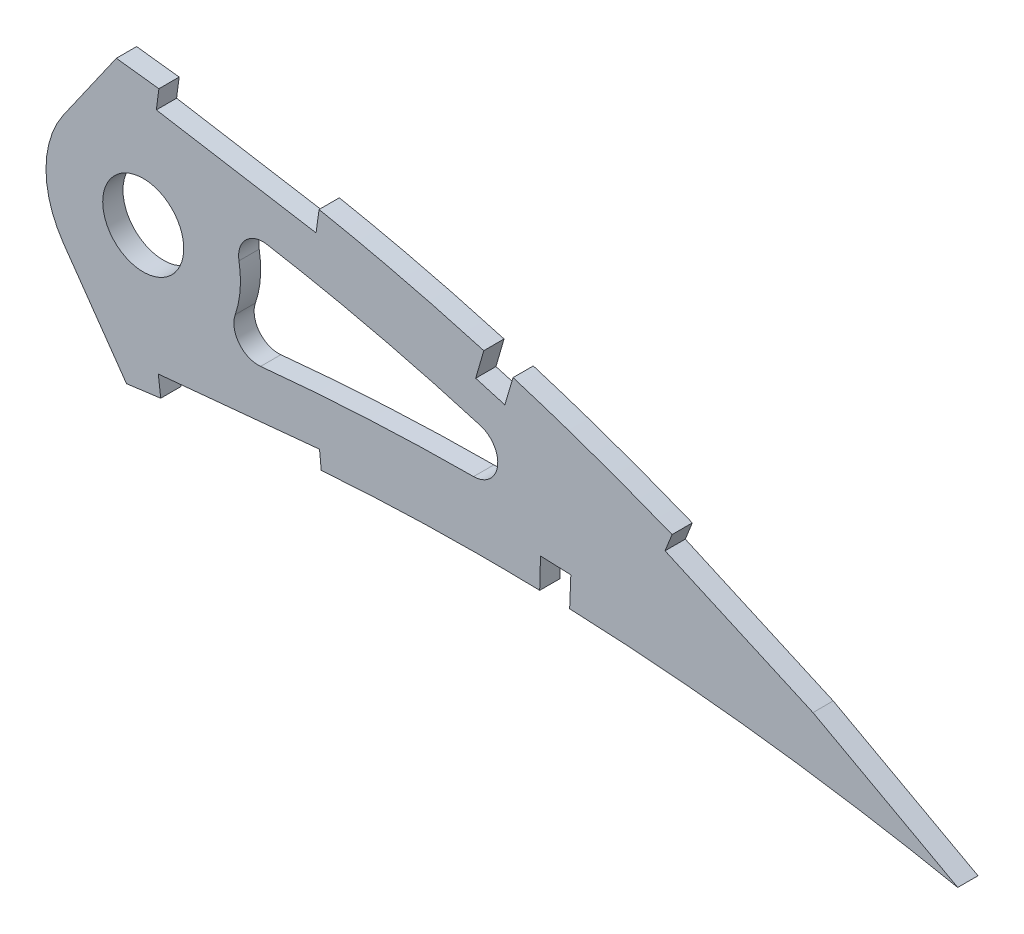
SolidWorks part; units mm, degrees
ref_plane "Front Plane" through (0, 0, 0) normal (0, 0, 1) x (1, 0, 0)
ref_plane "Top Plane" through (0, 0, 0) normal (0, 1, 0) x (1, 0, 0)
ref_plane "Right Plane" through (0, 0, 0) normal (1, 0, 0) x (0, 0, -1)
curve "Curve1"
  spline degree 3 poles (418.0125, 0.6517, 0) (417.9804, 0.6715, 0) (417.8525, 0.7505, 0) (417.5642, 0.9274, 0) (417.084, 1.2219, 0) (416.4119, 1.6322, 0) (415.5483, 2.157, 0) (414.4927, 2.7927, 0) (413.2459, 3.5372, 0) (411.8081, 4.387, 0) (410.1795, 5.3382, 0) (408.3608, 6.3869, 0) (406.352, 7.527, 0) (404.1539, 8.7541, 0) (401.7673, 10.0622, 0) (399.1927, 11.4455, 0) (396.4309, 12.8968, 0) (393.4831, 14.4101, 0) (390.3497, 15.9768, 0) (387.0323, 17.5905, 0) (383.532, 19.2431, 0) (379.8498, 20.9259, 0) (375.9881, 22.6319, 0) (371.9478, 24.3506, 0) (367.7312, 26.0745, 0) (363.3401, 27.7938, 0) (358.7771, 29.5006, 0) (354.0441, 31.184, 0) (349.1444, 32.8365, 0) (344.0806, 34.4474, 0) (338.8562, 36.008, 0) (333.4742, 37.5082, 0) (327.9392, 38.9402, 0) (322.2547, 40.2936, 0) (316.4254, 41.5594, 0) (310.456, 42.7299, 0) (304.3515, 43.7936, 0) (298.1289, 44.7494, 0) (291.8882, 45.5445, 0) (285.6603, 46.3243, 0) (279.4418, 47.0569, 0) (273.1472, 47.7584, 0) (266.7827, 48.425, 0) (260.3545, 49.0544, 0) (253.8692, 49.6441, 0) (247.3335, 50.1923, 0) (240.7538, 50.6959, 0) (234.1369, 51.1541, 0) (227.4895, 51.5628, 0) (220.8185, 51.9218, 0) (214.1308, 52.2286, 0) (207.4334, 52.481, 0) (200.7332, 52.6776, 0) (194.0374, 52.8164, 0) (187.3531, 52.8966, 0) (180.6873, 52.916, 0) (174.0473, 52.8742, 0) (167.44, 52.7698, 0) (160.8726, 52.6014, 0) (154.3521, 52.3686, 0) (147.8856, 52.0716, 0) (141.4801, 51.7078, 0) (135.1426, 51.2797, 0) (128.8802, 50.7853, 0) (122.6997, 50.2246, 0) (116.6076, 49.5999, 0) (110.6107, 48.9095, 0) (104.7154, 48.1553, 0) (98.9282, 47.3389, 0) (93.2555, 46.4598, 0) (87.7035, 45.5205, 0) (82.2781, 44.522, 0) (76.9851, 43.4673, 0) (71.8302, 42.3565, 0) (66.8189, 41.1931, 0) (61.9564, 39.979, 0) (57.2479, 38.7165, 0) (52.6982, 37.4086, 0) (48.3119, 36.0583, 0) (44.0941, 34.667, 0) (40.048, 33.2401, 0) (36.1786, 31.7785, 0) (32.4888, 30.2868, 0) (28.983, 28.767, 0) (25.6637, 27.2237, 0) (22.5348, 25.6586, 0) (19.5984, 24.0762, 0) (16.8576, 22.4789, 0) (14.3149, 20.8697, 0) (11.9714, 19.2526, 0) (9.8303, 17.6287, 0) (7.8925, 16.002, 0) (6.159, 14.375, 0) (4.6325, 12.7489, 0) (3.3127, 11.1265, 0) (2.2016, 9.5091, 0) (1.2991, 7.8983, 0) (0.6075, 6.2951, 0) (0.126, 4.7006, 0) (-0.1376, 3.117, 0) (-0.2032, 1.5431, 0) (-0.0676, 0.5136, 0) (0, 0, 0) knots 0 0 0 0 0.000254 0.001015 0.002283 0.004057 0.006331 0.009105 0.012374 0.016134 0.02038 0.025106 0.030306 0.035972 0.0421 0.048678 0.055702 0.06316 0.071046 0.07935 0.088063 0.097176 0.106678 0.116562 0.126814 0.137428 0.148394 0.1597 0.171338 0.183298 0.19557 0.208144 0.221012 0.234162 0.247587 0.261277 0.275223 0.289414 0.303771 0.317689 0.331784 0.34604 0.360444 0.374983 0.38964 0.404403 0.419257 0.434187 0.449177 0.464215 0.479284 0.49437 0.509458 0.524532 0.539579 0.554583 0.56953 0.584403 0.599191 0.613877 0.628447 0.642889 0.657186 0.671326 0.685294 0.699078 0.712665 0.726043 0.739198 0.752118 0.764792 0.777208 0.789356 0.801224 0.812804 0.824083 0.835055 0.84571 0.856038 0.866034 0.875689 0.884998 0.893953 0.902553 0.910789 0.918661 0.926166 0.933303 0.940071 0.946475 0.952518 0.958205 0.963547 0.968557 0.97325 0.977651 0.981787 0.985694 0.989415 0.993001 0.996508 1 1 1 1
curve "Curve2"
  spline degree 3 poles (0, 0, 0) (0.1073, -0.5067, 0) (0.3225, -1.5225, 0) (0.9071, -2.9849, 0) (1.6803, -4.3906, 0) (2.6581, -5.736, 0) (3.8343, -7.0207, 0) (5.206, -8.246, 0) (6.772, -9.4112, 0) (8.5303, -10.5159, 0) (10.4783, -11.5612, 0) (12.6138, -12.5465, 0) (14.9348, -13.4715, 0) (17.4389, -14.3348, 0) (20.1229, -15.1379, 0) (22.9843, -15.8787, 0) (26.0199, -16.5584, 0) (29.2267, -17.1751, 0) (32.6013, -17.7296, 0) (36.1401, -18.2214, 0) (39.8395, -18.651, 0) (43.6959, -19.0173, 0) (47.7054, -19.3212, 0) (51.8641, -19.5629, 0) (56.168, -19.7432, 0) (60.6128, -19.8613, 0) (65.1943, -19.9191, 0) (69.9083, -19.9175, 0) (74.7502, -19.8561, 0) (79.7159, -19.7382, 0) (84.8006, -19.5631, 0) (89.9997, -19.3329, 0) (95.3085, -19.05, 0) (100.7222, -18.7153, 0) (106.2362, -18.3302, 0) (111.8455, -17.8979, 0) (117.5452, -17.4195, 0) (123.3302, -16.8976, 0) (129.1955, -16.3351, 0) (135.1358, -15.7335, 0) (141.1461, -15.0958, 0) (147.221, -14.4241, 0) (153.3552, -13.7218, 0) (159.5432, -12.9903, 0) (165.7798, -12.2338, 0) (172.059, -11.4536, 0) (178.3757, -10.6529, 0) (184.7241, -9.8353, 0) (191.0984, -9.0009, 0) (197.493, -8.1554, 0) (203.902, -7.2983, 0) (210.3197, -6.4339, 0) (216.7401, -5.5649, 0) (223.157, -4.6917, 0) (229.5648, -3.8177, 0) (235.9575, -2.9455, 0) (242.3289, -2.075, 0) (248.6732, -1.2107, 0) (254.984, -0.3523, 0) (261.2554, 0.4983, 0) (267.4816, 1.3385, 0) (273.6565, 2.1675, 0) (279.7739, 2.9846, 0) (285.8276, 3.7901, 0) (291.7208, 4.5595, 0) (297.4382, 5.334, 0) (302.999, 5.9689, 0) (308.4906, 6.5107, 0) (313.9186, 6.955, 0) (319.2766, 7.3081, 0) (324.5584, 7.5724, 0) (329.7577, 7.7517, 0) (334.868, 7.8514, 0) (339.8828, 7.8739, 0) (344.7953, 7.8264, 0) (349.5992, 7.7127, 0) (354.2877, 7.538, 0) (358.8543, 7.3082, 0) (363.2925, 7.0294, 0) (367.5956, 6.7058, 0) (371.7576, 6.345, 0) (375.7722, 5.9523, 0) (379.6331, 5.5321, 0) (383.3347, 5.0933, 0) (386.8711, 4.6386, 0) (390.237, 4.1757, 0) (393.427, 3.7092, 0) (396.4359, 3.245, 0) (399.2592, 2.7876, 0) (401.8921, 2.3431, 0) (404.3306, 1.9155, 0) (406.5705, 1.5092, 0) (408.6087, 1.1291, 0) (410.4411, 0.7773, 0) (412.0652, 0.4594, 0) (413.4782, 0.1769, 0) (414.6777, -0.0662, 0) (415.6619, -0.269, 0) (416.4292, -0.4281, 0) (416.9781, -0.5438, 0) (417.3079, -0.6126, 0) (417.4545, -0.6439, 0) (417.4911, -0.6517, 0) knots 0 0 0 0 0.003638 0.007293 0.011028 0.014901 0.018963 0.023258 0.027821 0.032679 0.037853 0.043362 0.049215 0.055422 0.061989 0.068918 0.076211 0.083868 0.091887 0.100266 0.109 0.118085 0.127515 0.137285 0.147388 0.157816 0.168563 0.179619 0.190977 0.202627 0.21456 0.226767 0.239236 0.251959 0.264924 0.27812 0.291536 0.30516 0.318981 0.332985 0.347163 0.361499 0.375981 0.390597 0.405333 0.420175 0.43511 0.450124 0.465203 0.480333 0.495501 0.51069 0.525887 0.541078 0.556247 0.571382 0.586466 0.601485 0.616424 0.631269 0.646007 0.660621 0.675098 0.689423 0.703582 0.716908 0.730009 0.742952 0.755726 0.76832 0.780724 0.792927 0.804916 0.816679 0.828204 0.839475 0.850481 0.861208 0.871639 0.881763 0.891564 0.901027 0.910139 0.918884 0.927249 0.935221 0.942785 0.949928 0.956638 0.962904 0.968712 0.974054 0.978918 0.983297 0.98718 0.990561 0.993433 0.995791 0.99763 0.998946 0.999737 1 1 1 1
sketch "Sketch1" plane through (0, 0, 0) normal (0, 0, 1) x (1, 0, 0)
  line L25 (417.4911, -0.6517) -> (421.451, -1.4725)
  line L26 (418.0125, 0.6517) -> (421.451, -1.4725)
  spline S2 degree 3 poles (-2901.6072, -758.8258) (62.2286, 60.9377) (-7.5382, 18.1399) (0.9071, -2.9849) (1.6803, -4.3906) (2.6581, -5.736) (3.8343, -7.0207) (5.206, -8.246) (6.772, -9.4112) (8.5303, -10.5159) (10.4783, -11.5612) (12.6138, -12.5465) (14.9348, -13.4715) (17.4389, -14.3348) (20.1229, -15.1379) (22.9843, -15.8787) (26.0199, -16.5584) (29.2267, -17.1751) (32.6013, -17.7296) (36.1401, -18.2214) (39.8395, -18.651) (43.6959, -19.0173) (47.7054, -19.3212) (51.8641, -19.5629) (56.168, -19.7432) (60.6128, -19.8613) (65.1943, -19.9191) (69.9083, -19.9175) (74.7502, -19.8561) (79.7159, -19.7382) (84.8006, -19.5631) (89.9997, -19.3329) (95.3085, -19.05) (100.7222, -18.7153) (106.2362, -18.3302) (111.8455, -17.8979) (117.5452, -17.4195) (123.3302, -16.8976) (129.1955, -16.3351) (135.1358, -15.7335) (141.1461, -15.0958) (147.221, -14.4241) (153.3552, -13.7218) (159.5432, -12.9903) (165.7798, -12.2338) (172.059, -11.4536) (178.3757, -10.6529) (184.7241, -9.8353) (191.0984, -9.0009) (197.493, -8.1554) (203.902, -7.2983) (210.3197, -6.4339) (216.7401, -5.5649) (223.157, -4.6917) (229.5648, -3.8177) (235.9575, -2.9455) (242.3289, -2.075) (248.6732, -1.2107) (254.984, -0.3523) (261.2554, 0.4983) (267.4816, 1.3385) (273.6565, 2.1675) (279.7739, 2.9846) (285.8276, 3.7901) (291.7208, 4.5595) (297.4382, 5.334) (302.999, 5.9689) (308.4906, 6.5107) (313.9186, 6.955) (319.2766, 7.3081) (324.5584, 7.5724) (329.7577, 7.7517) (334.868, 7.8514) (339.8828, 7.8739) (344.7953, 7.8264) (349.5992, 7.7127) (354.2877, 7.538) (358.8543, 7.3082) (363.2925, 7.0294) (367.5956, 6.7058) (371.7576, 6.345) (375.7722, 5.9523) (379.6331, 5.5321) (383.3347, 5.0933) (386.8711, 4.6386) (390.237, 4.1757) (393.427, 3.7092) (396.4359, 3.245) (399.2592, 2.7876) (401.8921, 2.3431) (404.3306, 1.9155) (406.5705, 1.5092) (408.6087, 1.1291) (410.4411, 0.7773) (412.0652, 0.4594) (413.4782, 0.1769) (414.6777, -0.0662) (415.6619, -0.269) (416.4292, -0.4281) (416.9781, -0.5438) (432.6216, -3.8089) (446.5682, -14.1933) (1083.8628, 2923.4074) knots -0.148283 -0.148283 -0.148283 -0.148283 0.003638 0.007293 0.011028 0.014901 0.018963 0.023258 0.027821 0.032679 0.037853 0.043362 0.049215 0.055422 0.061989 0.068918 0.076211 0.083868 0.091887 0.100266 0.109 0.118085 0.127515 0.137285 0.147388 0.157816 0.168563 0.179619 0.190977 0.202627 0.21456 0.226767 0.239236 0.251959 0.264924 0.27812 0.291536 0.30516 0.318981 0.332985 0.347163 0.361499 0.375981 0.390597 0.405333 0.420175 0.43511 0.450124 0.465203 0.480333 0.495501 0.51069 0.525887 0.541078 0.556247 0.571382 0.586466 0.601485 0.616424 0.631269 0.646007 0.660621 0.675098 0.689423 0.703582 0.716908 0.730009 0.742952 0.755726 0.76832 0.780724 0.792927 0.804916 0.816679 0.828204 0.839475 0.850481 0.861208 0.871639 0.881763 0.891564 0.901027 0.910139 0.918884 0.927249 0.935221 0.942785 0.949928 0.956638 0.962904 0.968712 0.974054 0.978918 0.983297 0.98718 0.990561 0.993433 0.995791 0.99763 0.998946 0.999737 1.110049 1.110049 1.110049 1.110049 only from (0, 0) to (417.4911, -0.6517) construction
  spline S3 degree 3 poles (2035.6651, 2526.3996) (444.3669, -23.2124) (432.7668, -8.3977) (417.5642, 0.9274) (417.084, 1.2219) (416.4119, 1.6322) (415.5483, 2.157) (414.4927, 2.7927) (413.2459, 3.5372) (411.8081, 4.387) (410.1795, 5.3382) (408.3608, 6.3869) (406.352, 7.527) (404.1539, 8.7541) (401.7673, 10.0622) (399.1927, 11.4455) (396.4309, 12.8968) (393.4831, 14.4101) (390.3497, 15.9768) (387.0323, 17.5905) (383.532, 19.2431) (379.8498, 20.9259) (375.9881, 22.6319) (371.9478, 24.3506) (367.7312, 26.0745) (363.3401, 27.7938) (358.7771, 29.5006) (354.0441, 31.184) (349.1444, 32.8365) (344.0806, 34.4474) (338.8562, 36.008) (333.4742, 37.5082) (327.9392, 38.9402) (322.2547, 40.2936) (316.4254, 41.5594) (310.456, 42.7299) (304.3515, 43.7936) (298.1289, 44.7494) (291.8882, 45.5445) (285.6603, 46.3243) (279.4418, 47.0569) (273.1472, 47.7584) (266.7827, 48.425) (260.3545, 49.0544) (253.8692, 49.6441) (247.3335, 50.1923) (240.7538, 50.6959) (234.1369, 51.1541) (227.4895, 51.5628) (220.8185, 51.9218) (214.1308, 52.2286) (207.4334, 52.481) (200.7332, 52.6776) (194.0374, 52.8164) (187.3531, 52.8966) (180.6873, 52.916) (174.0473, 52.8742) (167.44, 52.7698) (160.8726, 52.6014) (154.3521, 52.3686) (147.8856, 52.0716) (141.4801, 51.7078) (135.1426, 51.2797) (128.8802, 50.7853) (122.6997, 50.2246) (116.6076, 49.5999) (110.6107, 48.9095) (104.7154, 48.1553) (98.9282, 47.3389) (93.2555, 46.4598) (87.7035, 45.5205) (82.2781, 44.522) (76.9851, 43.4673) (71.8302, 42.3565) (66.8189, 41.1931) (61.9564, 39.979) (57.2479, 38.7165) (52.6982, 37.4086) (48.3119, 36.0583) (44.0941, 34.667) (40.048, 33.2401) (36.1786, 31.7785) (32.4888, 30.2868) (28.983, 28.767) (25.6637, 27.2237) (22.5348, 25.6586) (19.5984, 24.0762) (16.8576, 22.4789) (14.3149, 20.8697) (11.9714, 19.2526) (9.8303, 17.6287) (7.8925, 16.002) (6.159, 14.375) (4.6325, 12.7489) (3.3127, 11.1265) (2.2016, 9.5091) (1.2991, 7.8983) (0.6075, 6.2951) (0.126, 4.7006) (-0.1376, 3.117) (-1.0834, -19.5745) (79.1081, -36.6721) (-2988.5065, -249.641) knots -0.11811 -0.11811 -0.11811 -0.11811 0.000254 0.001015 0.002283 0.004057 0.006331 0.009105 0.012374 0.016134 0.02038 0.025106 0.030306 0.035972 0.0421 0.048678 0.055702 0.06316 0.071046 0.07935 0.088063 0.097176 0.106678 0.116562 0.126814 0.137428 0.148394 0.1597 0.171338 0.183298 0.19557 0.208144 0.221012 0.234162 0.247587 0.261277 0.275223 0.289414 0.303771 0.317689 0.331784 0.34604 0.360444 0.374983 0.38964 0.404403 0.419257 0.434187 0.449177 0.464215 0.479284 0.49437 0.509458 0.524532 0.539579 0.554583 0.56953 0.584403 0.599191 0.613877 0.628447 0.642889 0.657186 0.671326 0.685294 0.699078 0.712665 0.726043 0.739198 0.752118 0.764792 0.777208 0.789356 0.801224 0.812804 0.824083 0.835055 0.84571 0.856038 0.866034 0.875689 0.884998 0.893953 0.902553 0.910789 0.918661 0.926166 0.933303 0.940071 0.946475 0.952518 0.958205 0.963547 0.968557 0.97325 0.977651 0.981787 0.985694 0.989415 0.993001 0.996508 1.142022 1.142022 1.142022 1.142022 only from (418.0125, 0.6517) to (0, 0) construction
  spline S4 degree 3 poles (0, 0) (0.1073, -0.5067) (0.3225, -1.5225) (0.9071, -2.9849) (1.6803, -4.3906) (2.6581, -5.736) (3.8343, -7.0207) (5.206, -8.246) (6.772, -9.4112) (8.5303, -10.5159) (10.4783, -11.5612) (12.6138, -12.5465) (14.9348, -13.4715) (17.4389, -14.3348) (20.1229, -15.1379) (22.9843, -15.8787) (26.0199, -16.5584) (29.2267, -17.1751) (32.6013, -17.7296) (36.1401, -18.2214) (39.8395, -18.651) (43.6959, -19.0173) (47.7054, -19.3212) (51.8641, -19.5629) (56.168, -19.7432) (60.6128, -19.8613) (65.1943, -19.9191) (69.9083, -19.9175) (74.7502, -19.8561) (79.7159, -19.7382) (84.8006, -19.5631) (89.9997, -19.3329) (95.3085, -19.05) (100.7222, -18.7153) (106.2362, -18.3302) (111.8455, -17.8979) (117.5452, -17.4195) (123.3302, -16.8976) (129.1955, -16.3351) (135.1358, -15.7335) (141.1461, -15.0958) (147.221, -14.4241) (153.3552, -13.7218) (159.5432, -12.9903) (165.7798, -12.2338) (172.059, -11.4536) (178.3757, -10.6529) (184.7241, -9.8353) (191.0984, -9.0009) (197.493, -8.1554) (203.902, -7.2983) (210.3197, -6.4339) (216.7401, -5.5649) (223.157, -4.6917) (229.5648, -3.8177) (235.9575, -2.9455) (242.3289, -2.075) (248.6732, -1.2107) (254.984, -0.3523) (261.2554, 0.4983) (267.4816, 1.3385) (273.6565, 2.1675) (279.7739, 2.9846) (285.8276, 3.7901) (291.7208, 4.5595) (297.4382, 5.334) (302.999, 5.9689) (308.4906, 6.5107) (313.9186, 6.955) (319.2766, 7.3081) (324.5584, 7.5724) (329.7577, 7.7517) (334.868, 7.8514) (339.8828, 7.8739) (344.7953, 7.8264) (349.5992, 7.7127) (354.2877, 7.538) (358.8543, 7.3082) (363.2925, 7.0294) (367.5956, 6.7058) (371.7576, 6.345) (375.7722, 5.9523) (379.6331, 5.5321) (383.3347, 5.0933) (386.8711, 4.6386) (390.237, 4.1757) (393.427, 3.7092) (396.4359, 3.245) (399.2592, 2.7876) (401.8921, 2.3431) (404.3306, 1.9155) (406.5705, 1.5092) (408.6087, 1.1291) (410.4411, 0.7773) (412.0652, 0.4594) (413.4782, 0.1769) (414.6777, -0.0662) (415.6619, -0.269) (416.4292, -0.4281) (416.9781, -0.5438) (417.3079, -0.6126) (417.4545, -0.6439) (417.4911, -0.6517) knots 0 0 0 0 0.003638 0.007293 0.011028 0.014901 0.018963 0.023258 0.027821 0.032679 0.037853 0.043362 0.049215 0.055422 0.061989 0.068918 0.076211 0.083868 0.091887 0.100266 0.109 0.118085 0.127515 0.137285 0.147388 0.157816 0.168563 0.179619 0.190977 0.202627 0.21456 0.226767 0.239236 0.251959 0.264924 0.27812 0.291536 0.30516 0.318981 0.332985 0.347163 0.361499 0.375981 0.390597 0.405333 0.420175 0.43511 0.450124 0.465203 0.480333 0.495501 0.51069 0.525887 0.541078 0.556247 0.571382 0.586466 0.601485 0.616424 0.631269 0.646007 0.660621 0.675098 0.689423 0.703582 0.716908 0.730009 0.742952 0.755726 0.76832 0.780724 0.792927 0.804916 0.816679 0.828204 0.839475 0.850481 0.861208 0.871639 0.881763 0.891564 0.901027 0.910139 0.918884 0.927249 0.935221 0.942785 0.949928 0.956638 0.962904 0.968712 0.974054 0.978918 0.983297 0.98718 0.990561 0.993433 0.995791 0.99763 0.998946 0.999737 1 1 1 1
  spline S5 degree 3 poles (418.0125, 0.6517) (417.9804, 0.6715) (417.8525, 0.7505) (417.5642, 0.9274) (417.084, 1.2219) (416.4119, 1.6322) (415.5483, 2.157) (414.4927, 2.7927) (413.2459, 3.5372) (411.8081, 4.387) (410.1795, 5.3382) (408.3608, 6.3869) (406.352, 7.527) (404.1539, 8.7541) (401.7673, 10.0622) (399.1927, 11.4455) (396.4309, 12.8968) (393.4831, 14.4101) (390.3497, 15.9768) (387.0323, 17.5905) (383.532, 19.2431) (379.8498, 20.9259) (375.9881, 22.6319) (371.9478, 24.3506) (367.7312, 26.0745) (363.3401, 27.7938) (358.7771, 29.5006) (354.0441, 31.184) (349.1444, 32.8365) (344.0806, 34.4474) (338.8562, 36.008) (333.4742, 37.5082) (327.9392, 38.9402) (322.2547, 40.2936) (316.4254, 41.5594) (310.456, 42.7299) (304.3515, 43.7936) (298.1289, 44.7494) (291.8882, 45.5445) (285.6603, 46.3243) (279.4418, 47.0569) (273.1472, 47.7584) (266.7827, 48.425) (260.3545, 49.0544) (253.8692, 49.6441) (247.3335, 50.1923) (240.7538, 50.6959) (234.1369, 51.1541) (227.4895, 51.5628) (220.8185, 51.9218) (214.1308, 52.2286) (207.4334, 52.481) (200.7332, 52.6776) (194.0374, 52.8164) (187.3531, 52.8966) (180.6873, 52.916) (174.0473, 52.8742) (167.44, 52.7698) (160.8726, 52.6014) (154.3521, 52.3686) (147.8856, 52.0716) (141.4801, 51.7078) (135.1426, 51.2797) (128.8802, 50.7853) (122.6997, 50.2246) (116.6076, 49.5999) (110.6107, 48.9095) (104.7154, 48.1553) (98.9282, 47.3389) (93.2555, 46.4598) (87.7035, 45.5205) (82.2781, 44.522) (76.9851, 43.4673) (71.8302, 42.3565) (66.8189, 41.1931) (61.9564, 39.979) (57.2479, 38.7165) (52.6982, 37.4086) (48.3119, 36.0583) (44.0941, 34.667) (40.048, 33.2401) (36.1786, 31.7785) (32.4888, 30.2868) (28.983, 28.767) (25.6637, 27.2237) (22.5348, 25.6586) (19.5984, 24.0762) (16.8576, 22.4789) (14.3149, 20.8697) (11.9714, 19.2526) (9.8303, 17.6287) (7.8925, 16.002) (6.159, 14.375) (4.6325, 12.7489) (3.3127, 11.1265) (2.2016, 9.5091) (1.2991, 7.8983) (0.6075, 6.2951) (0.126, 4.7006) (-0.1376, 3.117) (-0.2032, 1.5431) (-0.0676, 0.5136) (0, 0) knots 0 0 0 0 0.000254 0.001015 0.002283 0.004057 0.006331 0.009105 0.012374 0.016134 0.02038 0.025106 0.030306 0.035972 0.0421 0.048678 0.055702 0.06316 0.071046 0.07935 0.088063 0.097176 0.106678 0.116562 0.126814 0.137428 0.148394 0.1597 0.171338 0.183298 0.19557 0.208144 0.221012 0.234162 0.247587 0.261277 0.275223 0.289414 0.303771 0.317689 0.331784 0.34604 0.360444 0.374983 0.38964 0.404403 0.419257 0.434187 0.449177 0.464215 0.479284 0.49437 0.509458 0.524532 0.539579 0.554583 0.56953 0.584403 0.599191 0.613877 0.628447 0.642889 0.657186 0.671326 0.685294 0.699078 0.712665 0.726043 0.739198 0.752118 0.764792 0.777208 0.789356 0.801224 0.812804 0.824083 0.835055 0.84571 0.856038 0.866034 0.875689 0.884998 0.893953 0.902553 0.910789 0.918661 0.926166 0.933303 0.940071 0.946475 0.952518 0.958205 0.963547 0.968557 0.97325 0.977651 0.981787 0.985694 0.989415 0.993001 0.996508 1 1 1 1
extrude "Boss-Extrude1" add sketch "Sketch1" along normal blind 3.175
sketch "Sketch3" plane through (0, 0, 0) normal (0, 0, -1) x (-1, 0, 0)
  circle A1 centre (-285.7292, 26.2554) radius 6.35
extrude "Cut-Extrude2" cut sketch "Sketch3" against normal blind 7.62
sketch "Sketch4" plane through (0, 0, 3.175) normal (0, 0, 1) x (1, 0, 0)
  line L0 (273.2453, 34.9967) -> (281.5171, 46.8101)
  line L1 (273.2453, 17.5141) -> (283.1086, 3.4278)
  line L2 (285.7292, 26.2554) -> (311.044, 26.2554)
  circle A0 centre (285.7292, 26.2554) radius 6.35 construction
  circle A1 centre (285.7292, 26.2554) radius 6.35
  circle A2 centre (285.7292, 26.2554) radius 15.24
  spline S0 degree 3 poles (-1937.7253, -493.2296) (46.5589, 50.9528) (-6.5452, 15.6559) (0.9071, -2.9849) (1.6803, -4.3906) (2.6581, -5.736) (3.8343, -7.0207) (5.206, -8.246) (6.772, -9.4112) (8.5303, -10.5159) (10.4783, -11.5612) (12.6138, -12.5465) (14.9348, -13.4715) (17.4389, -14.3348) (20.1229, -15.1379) (22.9843, -15.8787) (26.0199, -16.5584) (29.2267, -17.1751) (32.6013, -17.7296) (36.1401, -18.2214) (39.8395, -18.651) (43.6959, -19.0173) (47.7054, -19.3212) (51.8641, -19.5629) (56.168, -19.7432) (60.6128, -19.8613) (65.1943, -19.9191) (69.9083, -19.9175) (74.7502, -19.8561) (79.7159, -19.7382) (84.8006, -19.5631) (89.9997, -19.3329) (95.3085, -19.05) (100.7222, -18.7153) (106.2362, -18.3302) (111.8455, -17.8979) (117.5452, -17.4195) (123.3302, -16.8976) (129.1955, -16.3351) (135.1358, -15.7335) (141.1461, -15.0958) (147.221, -14.4241) (153.3552, -13.7218) (159.5432, -12.9903) (165.7798, -12.2338) (172.059, -11.4536) (178.3757, -10.6529) (184.7241, -9.8353) (191.0984, -9.0009) (197.493, -8.1554) (203.902, -7.2983) (210.3197, -6.4339) (216.7401, -5.5649) (223.157, -4.6917) (229.5648, -3.8177) (235.9575, -2.9455) (242.3289, -2.075) (248.6732, -1.2107) (254.984, -0.3523) (261.2554, 0.4983) (267.4816, 1.3385) (273.6565, 2.1675) (279.7739, 2.9846) (285.8276, 3.7901) (291.7208, 4.5595) (297.4382, 5.334) (302.999, 5.9689) (308.4906, 6.5107) (313.9186, 6.955) (319.2766, 7.3081) (324.5584, 7.5724) (329.7577, 7.7517) (334.868, 7.8514) (339.8828, 7.8739) (344.7953, 7.8264) (349.5992, 7.7127) (354.2877, 7.538) (358.8543, 7.3082) (363.2925, 7.0294) (367.5956, 6.7058) (371.7576, 6.345) (375.7722, 5.9523) (379.6331, 5.5321) (383.3347, 5.0933) (386.8711, 4.6386) (390.237, 4.1757) (393.427, 3.7092) (396.4359, 3.245) (399.2592, 2.7876) (401.8921, 2.3431) (404.3306, 1.9155) (406.5705, 1.5092) (408.6087, 1.1291) (410.4411, 0.7773) (412.0652, 0.4594) (413.4782, 0.1769) (414.6777, -0.0662) (415.6619, -0.269) (416.4292, -0.4281) (416.9781, -0.5438) (430.6853, -3.4047) (443.0511, -11.7044) (871.2046, 1946.5522) knots -0.129551 -0.129551 -0.129551 -0.129551 0.003638 0.007293 0.011028 0.014901 0.018963 0.023258 0.027821 0.032679 0.037853 0.043362 0.049215 0.055422 0.061989 0.068918 0.076211 0.083868 0.091887 0.100266 0.109 0.118085 0.127515 0.137285 0.147388 0.157816 0.168563 0.179619 0.190977 0.202627 0.21456 0.226767 0.239236 0.251959 0.264924 0.27812 0.291536 0.30516 0.318981 0.332985 0.347163 0.361499 0.375981 0.390597 0.405333 0.420175 0.43511 0.450124 0.465203 0.480333 0.495501 0.51069 0.525887 0.541078 0.556247 0.571382 0.586466 0.601485 0.616424 0.631269 0.646007 0.660621 0.675098 0.689423 0.703582 0.716908 0.730009 0.742952 0.755726 0.76832 0.780724 0.792927 0.804916 0.816679 0.828204 0.839475 0.850481 0.861208 0.871639 0.881763 0.891564 0.901027 0.910139 0.918884 0.927249 0.935221 0.942785 0.949928 0.956638 0.962904 0.968712 0.974054 0.978918 0.983297 0.98718 0.990561 0.993433 0.995791 0.99763 0.998946 0.999737 1.096134 1.096134 1.096134 1.096134 only from (0, 0) to (417.4911, -0.6517) construction
  spline S1 degree 3 poles (1505.5404, 1678.541) (441.4039, -19.5852) (430.8807, -7.2408) (417.5642, 0.9274) (417.084, 1.2219) (416.4119, 1.6322) (415.5483, 2.157) (414.4927, 2.7927) (413.2459, 3.5372) (411.8081, 4.387) (410.1795, 5.3382) (408.3608, 6.3869) (406.352, 7.527) (404.1539, 8.7541) (401.7673, 10.0622) (399.1927, 11.4455) (396.4309, 12.8968) (393.4831, 14.4101) (390.3497, 15.9768) (387.0323, 17.5905) (383.532, 19.2431) (379.8498, 20.9259) (375.9881, 22.6319) (371.9478, 24.3506) (367.7312, 26.0745) (363.3401, 27.7938) (358.7771, 29.5006) (354.0441, 31.184) (349.1444, 32.8365) (344.0806, 34.4474) (338.8562, 36.008) (333.4742, 37.5082) (327.9392, 38.9402) (322.2547, 40.2936) (316.4254, 41.5594) (310.456, 42.7299) (304.3515, 43.7936) (298.1289, 44.7494) (291.8882, 45.5445) (285.6603, 46.3243) (279.4418, 47.0569) (273.1472, 47.7584) (266.7827, 48.425) (260.3545, 49.0544) (253.8692, 49.6441) (247.3335, 50.1923) (240.7538, 50.6959) (234.1369, 51.1541) (227.4895, 51.5628) (220.8185, 51.9218) (214.1308, 52.2286) (207.4334, 52.481) (200.7332, 52.6776) (194.0374, 52.8164) (187.3531, 52.8966) (180.6873, 52.916) (174.0473, 52.8742) (167.44, 52.7698) (160.8726, 52.6014) (154.3521, 52.3686) (147.8856, 52.0716) (141.4801, 51.7078) (135.1426, 51.2797) (128.8802, 50.7853) (122.6997, 50.2246) (116.6076, 49.5999) (110.6107, 48.9095) (104.7154, 48.1553) (98.9282, 47.3389) (93.2555, 46.4598) (87.7035, 45.5205) (82.2781, 44.522) (76.9851, 43.4673) (71.8302, 42.3565) (66.8189, 41.1931) (61.9564, 39.979) (57.2479, 38.7165) (52.6982, 37.4086) (48.3119, 36.0583) (44.0941, 34.667) (40.048, 33.2401) (36.1786, 31.7785) (32.4888, 30.2868) (28.983, 28.767) (25.6637, 27.2237) (22.5348, 25.6586) (19.5984, 24.0762) (16.8576, 22.4789) (14.3149, 20.8697) (11.9714, 19.2526) (9.8303, 17.6287) (7.8925, 16.002) (6.159, 14.375) (4.6325, 12.7489) (3.3127, 11.1265) (2.2016, 9.5091) (1.2991, 7.8983) (0.6075, 6.2951) (0.126, 4.7006) (-0.1376, 3.117) (-0.9722, -16.9072) (60.9773, -32.4825) (-1991.3982, -179.4503) knots -0.103174 -0.103174 -0.103174 -0.103174 0.000254 0.001015 0.002283 0.004057 0.006331 0.009105 0.012374 0.016134 0.02038 0.025106 0.030306 0.035972 0.0421 0.048678 0.055702 0.06316 0.071046 0.07935 0.088063 0.097176 0.106678 0.116562 0.126814 0.137428 0.148394 0.1597 0.171338 0.183298 0.19557 0.208144 0.221012 0.234162 0.247587 0.261277 0.275223 0.289414 0.303771 0.317689 0.331784 0.34604 0.360444 0.374983 0.38964 0.404403 0.419257 0.434187 0.449177 0.464215 0.479284 0.49437 0.509458 0.524532 0.539579 0.554583 0.56953 0.584403 0.599191 0.613877 0.628447 0.642889 0.657186 0.671326 0.685294 0.699078 0.712665 0.726043 0.739198 0.752118 0.764792 0.777208 0.789356 0.801224 0.812804 0.824083 0.835055 0.84571 0.856038 0.866034 0.875689 0.884998 0.893953 0.902553 0.910789 0.918661 0.926166 0.933303 0.940071 0.946475 0.952518 0.958205 0.963547 0.968557 0.97325 0.977651 0.981787 0.985694 0.989415 0.993001 0.996508 1.124083 1.124083 1.124083 1.124083 only from (418.0125, 0.6517) to (0, 0) construction
  spline S2 degree 3 poles (180.4181, -10.3891) (181.8505, -10.2052) (185.4085, -9.7457) (191.0984, -9.0009) (197.493, -8.1554) (203.902, -7.2983) (210.3197, -6.4339) (216.7401, -5.5649) (223.157, -4.6917) (229.5648, -3.8177) (235.9575, -2.9455) (242.3289, -2.075) (248.6732, -1.2107) (254.984, -0.3523) (261.2554, 0.4983) (267.4816, 1.3385) (273.6565, 2.1675) (279.7739, 2.9846) (285.8276, 3.7901) (291.7208, 4.5595) (297.4382, 5.334) (302.999, 5.9689) (308.4906, 6.5107) (313.9186, 6.955) (319.2766, 7.3081) (324.5584, 7.5724) (329.7577, 7.7517) (334.868, 7.8514) (339.8828, 7.8739) (344.7953, 7.8264) (349.5992, 7.7127) (354.2877, 7.538) (358.8543, 7.3082) (363.2925, 7.0294) (367.5956, 6.7058) (371.7576, 6.345) (375.7722, 5.9523) (379.6331, 5.5321) (383.3347, 5.0933) (386.8711, 4.6386) (390.237, 4.1757) (393.427, 3.7092) (396.4359, 3.245) (399.2592, 2.7876) (401.8921, 2.3431) (404.3306, 1.9155) (406.5705, 1.5092) (408.6087, 1.1291) (410.4411, 0.7773) (412.0652, 0.4594) (413.4782, 0.1769) (414.6777, -0.0662) (415.6619, -0.269) (416.4292, -0.4281) (416.9781, -0.5438) (417.3079, -0.6126) (417.4545, -0.6439) (417.4911, -0.6517) knots 0.439965 0.439965 0.439965 0.439965 0.450124 0.465203 0.480333 0.495501 0.51069 0.525887 0.541078 0.556247 0.571382 0.586466 0.601485 0.616424 0.631269 0.646007 0.660621 0.675098 0.689423 0.703582 0.716908 0.730009 0.742952 0.755726 0.76832 0.780724 0.792927 0.804916 0.816679 0.828204 0.839475 0.850481 0.861208 0.871639 0.881763 0.891564 0.901027 0.910139 0.918884 0.927249 0.935221 0.942785 0.949928 0.956638 0.962904 0.968712 0.974054 0.978918 0.983297 0.98718 0.990561 0.993433 0.995791 0.99763 0.998946 0.999737 1 1 1 1
  spline S3 degree 3 poles (418.0125, 0.6517) (417.9804, 0.6715) (417.8525, 0.7505) (417.5642, 0.9274) (417.084, 1.2219) (416.4119, 1.6322) (415.5483, 2.157) (414.4927, 2.7927) (413.2459, 3.5372) (411.8081, 4.387) (410.1795, 5.3382) (408.3608, 6.3869) (406.352, 7.527) (404.1539, 8.7541) (401.7673, 10.0622) (399.1927, 11.4455) (396.4309, 12.8968) (393.4831, 14.4101) (390.3497, 15.9768) (387.0323, 17.5905) (383.532, 19.2431) (379.8498, 20.9259) (375.9881, 22.6319) (371.9478, 24.3506) (367.7312, 26.0745) (363.3401, 27.7938) (358.7771, 29.5006) (354.0441, 31.184) (349.1444, 32.8365) (344.0806, 34.4474) (338.8562, 36.008) (333.4742, 37.5082) (327.9392, 38.9402) (322.2547, 40.2936) (316.4254, 41.5594) (310.456, 42.7299) (304.3515, 43.7936) (298.1289, 44.7494) (291.8882, 45.5445) (285.6603, 46.3243) (279.4418, 47.0569) (273.1472, 47.7584) (266.7827, 48.425) (260.3545, 49.0544) (253.8692, 49.6441) (247.3335, 50.1923) (240.7538, 50.6959) (234.1369, 51.1541) (227.4895, 51.5628) (220.8185, 51.9218) (214.1308, 52.2286) (207.4334, 52.481) (200.7332, 52.6776) (194.0374, 52.8164) (187.3531, 52.8966) (180.6873, 52.916) (174.0473, 52.8742) (167.44, 52.7698) (160.8726, 52.6014) (155.4817, 52.4089) (152.281, 52.2704) (151.2539, 52.2234) knots 0 0 0 0 0.000254 0.001015 0.002283 0.004057 0.006331 0.009105 0.012374 0.016134 0.02038 0.025106 0.030306 0.035972 0.0421 0.048678 0.055702 0.06316 0.071046 0.07935 0.088063 0.097176 0.106678 0.116562 0.126814 0.137428 0.148394 0.1597 0.171338 0.183298 0.19557 0.208144 0.221012 0.234162 0.247587 0.261277 0.275223 0.289414 0.303771 0.317689 0.331784 0.34604 0.360444 0.374983 0.38964 0.404403 0.419257 0.434187 0.449177 0.464215 0.479284 0.49437 0.509458 0.524532 0.539579 0.554583 0.56953 0.584403 0.599191 0.613877 0.620817 0.620817 0.620817 0.620817
  spline S4 degree 1 poles (412.6728, -7.992) (151.7184, 42.0741) knots 0 0 1 1 construction
  spline S5 degree 3 poles (412.6728, -7.992) (412.529, -7.9032) (412.2464, -7.7298) (411.6377, -7.3565) (410.5993, -6.7234) (408.5143, -5.4652) (404.306, -2.9803) (395.8163, 1.8196) (378.4768, 10.7592) (357.9235, 19.3569) (336.7625, 26.1844) (323.3258, 29.6855) (312.4652, 32.0171) (305.6501, 33.2719) (300.1537, 34.1638) (296.076, 34.7616) (291.9086, 35.3008) (286.2081, 36.0188) (279.1798, 36.867) (267.8599, 38.1235) (253.7183, 39.5037) (236.7158, 40.8444) (214.0351, 42.1902) (185.6608, 43.0017) (163.0284, 42.5917) (151.7184, 42.0741) knots 0 0 0 0 0.001213 0.002425 0.00485 0.0097 0.019401 0.038801 0.077602 0.155204 0.194005 0.232807 0.252207 0.271608 0.281308 0.291008 0.300708 0.310409 0.329809 0.34921 0.388011 0.426812 0.465613 0.543215 0.620817 0.620817 0.620817 0.620817
  spline S6 degree 1 poles (179.1239, -0.3119) (419.6107, 9.2848) knots 0 0 1 1 construction
  spline S7 degree 3 poles (179.1239, -0.3119) (188.9725, 0.9529) (208.644, 3.5759) (233.2881, 6.9462) (253.0144, 9.6358) (267.829, 11.6393) (278.9188, 13.1245) (286.3557, 14.1051) (290.0348, 14.5872) (293.7202, 15.0843) (297.5682, 15.5751) (301.3934, 16.0072) (306.4806, 16.5301) (315.4288, 17.2991) (328.2209, 17.9712) (343.5941, 18.1039) (364.063, 17.4008) (384.4368, 15.4184) (402.073, 12.6709) (410.8627, 11.0539) (415.2186, 10.1932) (417.2602, 9.7755) (418.1832, 9.5844) (418.673, 9.4822) (419.1054, 9.3912) (419.4468, 9.3197) (419.6107, 9.2848) knots 0.439965 0.439965 0.439965 0.439965 0.50997 0.579974 0.614976 0.649978 0.684981 0.693731 0.702482 0.711232 0.719983 0.728733 0.737484 0.754985 0.789987 0.824989 0.859991 0.929996 0.964998 0.982499 0.991249 0.995625 0.996719 0.997812 0.998906 1 1 1 1
  dimension "D2" = 30.48
  dimension "D1" = 10.16
  dimension "D3" = 55
  dimension "D4" = 55
extrude "Cut-Extrude3" cut sketch "Sketch4" against normal through all
sketch "Sketch5" plane through (0, 0, 3.175) normal (0, 0, 1) x (1, 0, 0)
  line L0 (313.2552, 41.8987) -> (288.194, 46.0769)
  line L1 (313.2552, 41.8987) -> (288.194, 46.0769)
  line L2 (288.194, 46.0769) -> (287.7828, 42.9291)
  line L3 (288.194, 46.0769) -> (287.7828, 42.9291)
  line L4 (313.3657, 9.6572) -> (288.0908, 7.2303)
  line L5 (313.3657, 9.6572) -> (288.0908, 7.2303)
  line L6 (288.0908, 7.2303) -> (288.4802, 4.0794)
  line L7 (288.0908, 7.2303) -> (288.4802, 4.0794)
  line L8 (343.7526, 34.7378) -> (339.168, 36.1061)
  line L9 (343.7526, 34.7378) -> (339.168, 36.1061)
  line L10 (339.168, 36.1061) -> (337.8421, 31.5325)
  line L11 (339.168, 36.1061) -> (337.8421, 31.5325)
  line L12 (352.7568, 12.3038) -> (347.9988, 12.4911)
  line L13 (352.7568, 12.3038) -> (347.9988, 12.4911)
  line L14 (347.9988, 12.4911) -> (347.8753, 7.7308)
  line L15 (347.9988, 12.4911) -> (347.8753, 7.7308)
  line L16 (391.886, 15.5301) -> (368.7011, 25.8958)
  line L17 (391.886, 15.5301) -> (368.7011, 25.8958)
  line L18 (368.7011, 25.8958) -> (367.5249, 22.9474)
  line L19 (368.7011, 25.8958) -> (367.5249, 22.9474)
  line L20 (414.5246, 3.1973) -> (392.2313, 15.3684)
  line L21 (414.5246, 3.1973) -> (392.2313, 15.3684)
  line L22 (413.0032, 0.4106) -> (414.5246, 3.1973)
  line L23 (413.0032, 0.4106) -> (414.5246, 3.1973)
  line L24 (390.7099, 12.5817) -> (413.0032, 0.4106)
  line L25 (390.7099, 12.5817) -> (413.0032, 0.4106)
  line L26 (367.5249, 22.9474) -> (390.7099, 12.5817)
  line L27 (367.5249, 22.9474) -> (390.7099, 12.5817)
  line L28 (352.5709, 7.5776) -> (352.7568, 12.3038)
  line L29 (352.5709, 7.5776) -> (352.7568, 12.3038)
  line L30 (347.8753, 7.7308) -> (352.5709, 7.5776)
  line L31 (347.8753, 7.7308) -> (352.5709, 7.5776)
  line L32 (342.4157, 30.2065) -> (343.7526, 34.7378)
  line L33 (342.4157, 30.2065) -> (343.7526, 34.7378)
  line L34 (337.8421, 31.5325) -> (342.4157, 30.2065)
  line L35 (337.8421, 31.5325) -> (342.4157, 30.2065)
  line L36 (287.7828, 42.9291) -> (312.8213, 38.7536)
  line L37 (287.7828, 42.9291) -> (312.8213, 38.7536)
  line L38 (312.8213, 38.7536) -> (313.2552, 41.8987)
  line L39 (312.8213, 38.7536) -> (313.2552, 41.8987)
  line L40 (313.6697, 6.4979) -> (313.3657, 9.6572)
  line L41 (313.6697, 6.4979) -> (313.3657, 9.6572)
  line L42 (288.4802, 4.0794) -> (313.6697, 6.4979)
  line L43 (288.4802, 4.0794) -> (313.6697, 6.4979)
  line L44 (288.194, 46.0769) -> (288.7888, 50.3891)
  line L45 (313.2552, 41.8987) -> (313.8742, 46.386)
  line L46 (368.7011, 25.8958) -> (370.4349, 29.7738)
  line L47 (370.4349, 29.7738) -> (442.5317, 29.7738)
  line L48 (442.5317, 29.7738) -> (442.5317, -15.7106)
  line L49 (442.5317, -15.7106) -> (413.0032, 0.4106)
  line L50 (347.8753, 7.7308) -> (347.7745, 3.8459)
  line L51 (352.5709, 7.5776) -> (352.4057, 3.3777)
extrude "Cut-Extrude7" cut sketch "Sketch5" against normal through all
fillet "Fillet1" radius 3.81 3 edges at (362.3528, 17.2653, 1.5875) (298.6195, 34.3854, 1.5875) (296.4559, 15.4298, 1.5875)
move or copy body "Body-Move/Copy1" [suppressed] bodies to move or copy 120 parameters "D1"=0, "D2"=0, "D3"=0
move or copy body "Body-Move/Copy2" [suppressed] bodies to move or copy 121 parameters "D1"=0, "D2"=0, "D3"=0
